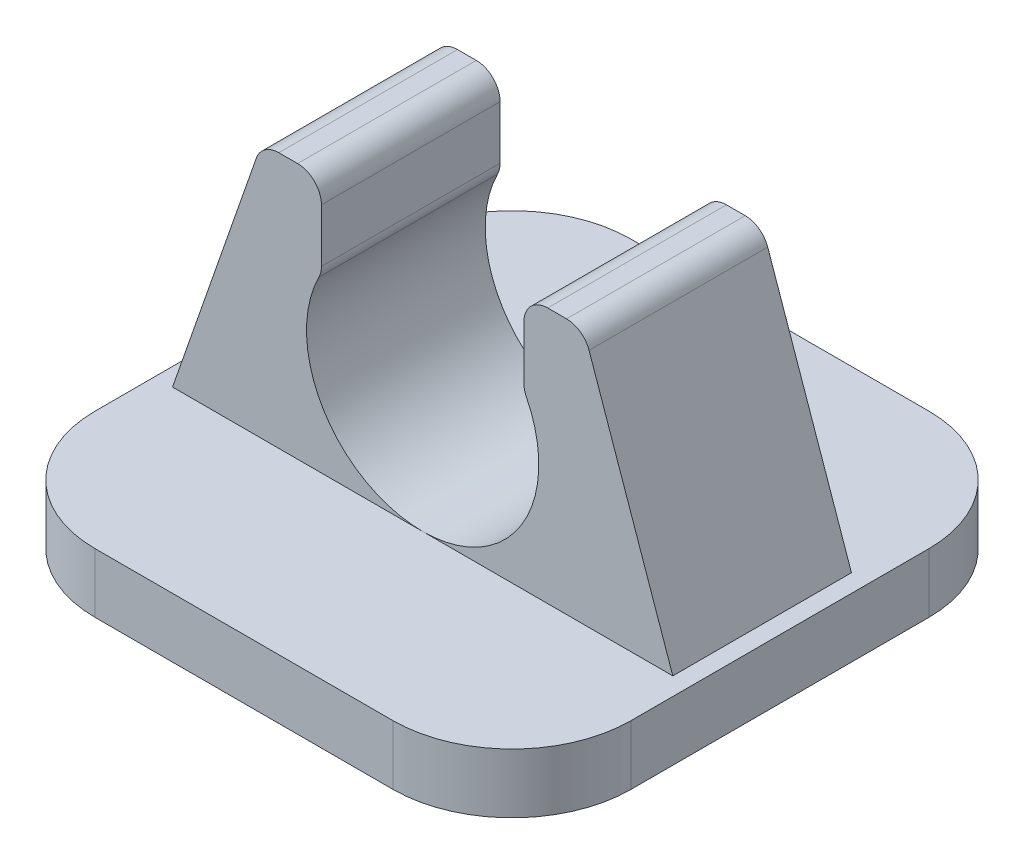
SolidWorks part; units mm, degrees
ref_plane "Front Plane" through (0, 0, 0) normal (0, 0, 1) x (1, 0, 0)
ref_plane "Top Plane" through (0, 0, 0) normal (0, 1, 0) x (1, 0, 0)
ref_plane "Right Plane" through (0, 0, 0) normal (1, 0, 0) x (0, 0, -1)
sketch "Sketch1" plane through (0, 0, 0) normal (0, 1, 0) x (1, 0, 0)
  line L1 (-4.5, -4.5) -> (4.5, -4.5)
  line L2 (-4.5, -4.5) -> (-4.5, 4.5)
  line L3 (-4.5, 4.5) -> (4.5, 4.5)
  line L4 (4.5, -4.5) -> (4.5, 4.5)
  line L5 (-4.5, -4.5) -> (4.5, 4.5) construction
  line L6 (-4.5, 4.5) -> (4.5, -4.5) construction
  point P0 (0, 0)
  dimension "D1" = 9
extrude "Boss-Extrude1" add sketch "Sketch1" along normal blind 1
ref_plane "Plane1" through (0, 0, 1.5) normal (0, 0, 1) x (1, 0, 0)
sketch "Sketch2" plane through (0, 0, 1.5) normal (0, 0, 1) x (1, 0, 0)
  line L0 (0, 1) -> (0, 2.95) construction
  line L1 (-4.5, 1) -> (4.5, 1) construction
  line L2 (-1.7, 3.9052) -> (1.7, 3.9052)
  line L3 (0, 3.9052) -> (0, 4.9) construction
  line L4 (1.7, 3.9052) -> (1.7, 5.3)
  line L5 (1.7, 5.3) -> (2.7, 5.3)
  line L6 (2.7, 5.3) -> (4.2, 1)
  line L7 (4.2, 1) -> (-4.2, 1)
  line L8 (-2.7, 5.3) -> (-4.2, 1)
  line L9 (-1.7, 5.3) -> (-2.7, 5.3)
  line L10 (-1.7, 3.9052) -> (-1.7, 5.3)
  circle A0 centre (0, 2.95) radius 1.95
  dimension "D1" = 3.9
  dimension "D2" = 1.95
  dimension "D3" = 3.4
  dimension "D4" = 1
  dimension "D5" = 1.5
  dimension "D6" = 4.3
extrude "Boss-Extrude2" add sketch "Sketch2" against normal blind 3 contours A0 L10 L9 L8 L7 | A0 L7 L6 L5 L4
fillet "Fillet1" radius 0.4 6 edges at (1.7, 3.9052, 0) (-1.7, 3.9052, 0) (2.7, 5.3, 0) (-2.7, 5.3, 0) (1.7, 5.3, 0) (-1.7, 5.3, 0)
fillet "Fillet2" radius 2 4 edges at (4.5, 0.5, 4.5) (-4.5, 0.5, 4.5) (-4.5, 0.5, -4.5) (4.5, 0.5, -4.5)
